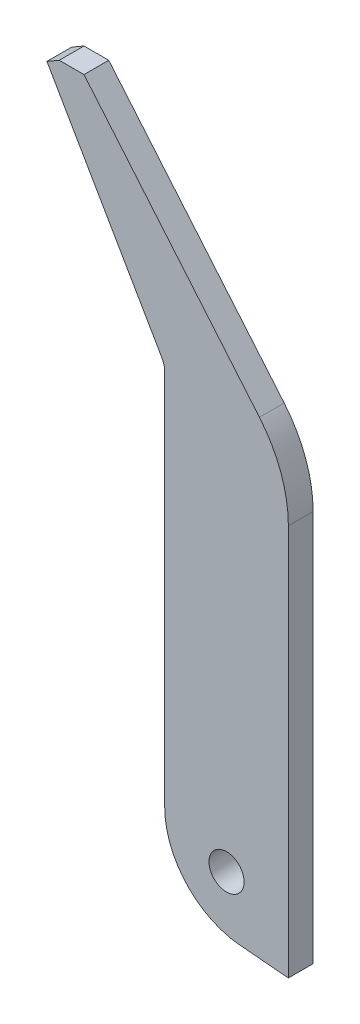
SolidWorks part; units mm, degrees
material "Plain Carbon Steel"
ref_plane "Спереди" through (0, 0, 0) normal (0, 0, 1) x (1, 0, 0)
ref_plane "Сверху" through (0, 0, 0) normal (0, 1, 0) x (1, 0, 0)
ref_plane "Справа" through (0, 0, 0) normal (1, 0, 0) x (0, 0, -1)
sketch "Sketch1" plane through (0, 0, 0) normal (0, 0, 1) x (1, 0, 0)
  line L0 (0, 0) -> (0, 95)
  line L1 (-7.0187, 114.2836) -> (-49.5748, 165)
  line L2 (-49.5748, 165) -> (-55.5748, 165)
  line L3 (-55.5748, 165) -> (-58.5748, 163.2679)
  line L4 (-58.5748, 163.2679) -> (-30.6699, 114.9353)
  line L5 (-30, 112.4353) -> (-30, 2.6247)
  line L6 (-30, 2.6247) -> (0, 0)
  arc A0 (0, 95) -> (-7.0187, 114.2836) centre (-30, 95) ccw
  arc A1 (-30.6699, 114.9353) -> (-30, 112.4353) centre (-35, 112.4353) cw
  circle A2 centre (-15, 14.8) radius 4.25
  dimension "D3" = 30
  dimension "D6" = 5
  dimension "D11" = 8.5
  dimension "D1" = 30
  dimension "D2" = 40
  dimension "D4" = 165
  dimension "D5" = 10
  dimension "D7" = 95
  dimension "D8" = 85
  dimension "D9" = 9
  dimension "D10" = 3
  dimension "D12" = 15
  dimension "D13" = 14.8
extrude "Extrude1" add sketch "Sketch1" along normal mid plane 6
fillet "Fillet1" radius 20 1 edges at (-30, 2.6247, 0)
